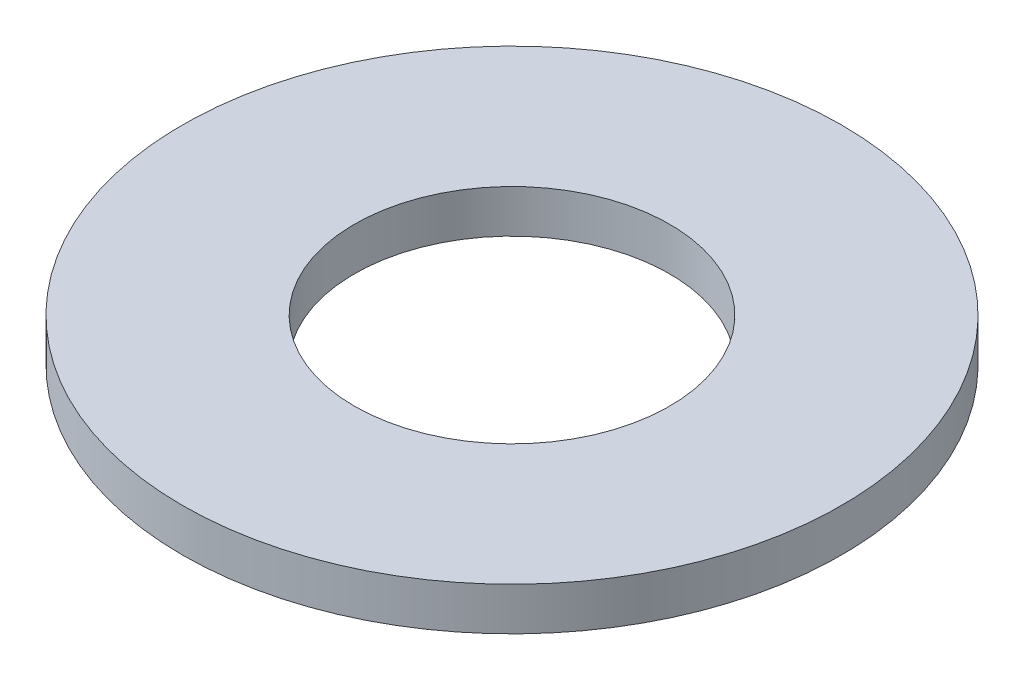
SolidWorks part; units mm, degrees
ref_plane "Front Plane" through (0, 0, 0) normal (0, 0, 1) x (1, 0, 0)
ref_plane "Top Plane" through (0, 0, 0) normal (0, 1, 0) x (1, 0, 0)
ref_plane "Right Plane" through (0, 0, 0) normal (1, 0, 0) x (0, 0, -1)
sketch "Sketch1" plane through (0, 0, 0) normal (0, 1, 0) x (1, 0, 0)
  circle A0 centre (0, 0) radius 23
  circle A1 centre (0, 0) radius 11
  dimension "D1" = 46
  dimension "D2" = 22
extrude "Boss-Extrude1" add sketch "Sketch1" along normal blind 3
